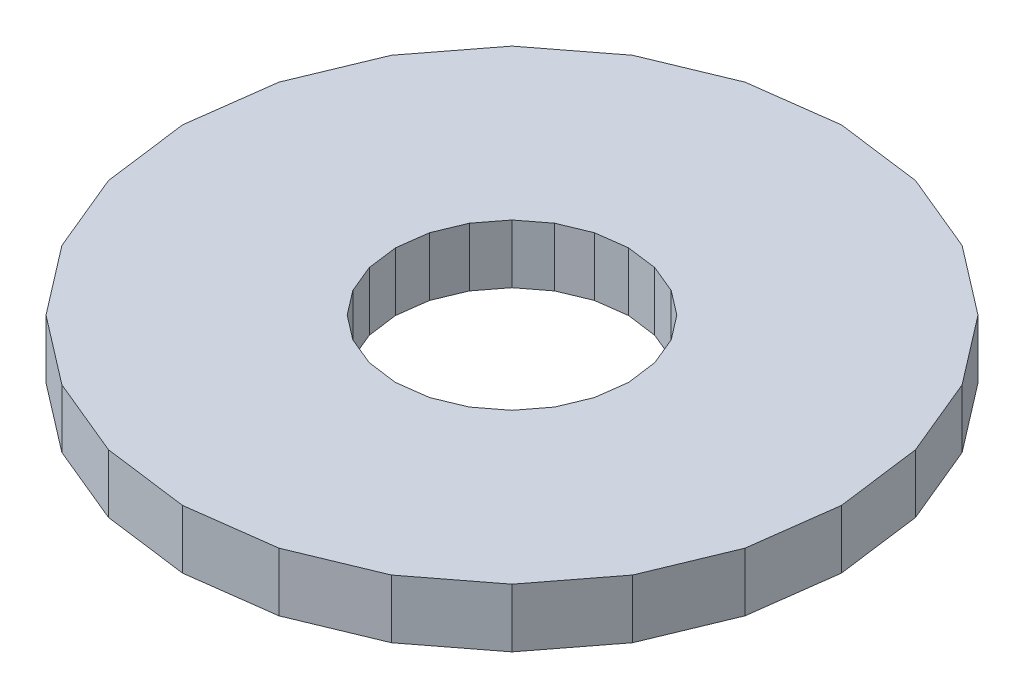
SolidWorks part; units mm, degrees
ref_plane "Front Plane" through (0, 0, 0) normal (0, 0, 1) x (1, 0, 0)
ref_plane "Top Plane" through (0, 0, 0) normal (0, 1, 0) x (1, 0, 0)
ref_plane "Right Plane" through (0, 0, 0) normal (1, 0, 0) x (0, 0, -1)
sketch "Sketch3" plane through (0, 0, 0) normal (0, 1, 0) x (1, 0, 0)
  line L0 (0, 0) -> (-37.8566, 0) construction
  line L1 (-107.0283, 0) -> (-103.3814, -27.701)
  line L2 (-103.3814, -27.701) -> (-92.6893, -53.5142)
  line L3 (-92.6893, -53.5142) -> (-75.6805, -75.6805)
  line L4 (-75.6805, -75.6805) -> (-53.5142, -92.6893)
  line L5 (-53.5142, -92.6893) -> (-27.701, -103.3814)
  line L6 (-27.701, -103.3814) -> (0, -107.0283)
  line L7 (0, -107.0283) -> (27.701, -103.3814)
  line L8 (27.701, -103.3814) -> (53.5142, -92.6893)
  line L9 (53.5142, -92.6893) -> (75.6805, -75.6805)
  line L10 (75.6805, -75.6805) -> (92.6893, -53.5142)
  line L11 (92.6893, -53.5142) -> (103.3814, -27.701)
  line L12 (103.3814, -27.701) -> (107.0283, 0)
  line L13 (107.0283, 0) -> (103.3814, 27.701)
  line L14 (103.3814, 27.701) -> (92.6893, 53.5142)
  line L15 (92.6893, 53.5142) -> (75.6805, 75.6805)
  line L16 (75.6805, 75.6805) -> (53.5142, 92.6893)
  line L17 (53.5142, 92.6893) -> (27.701, 103.3814)
  line L18 (27.701, 103.3814) -> (0, 107.0283)
  line L19 (0, 107.0283) -> (-27.701, 103.3814)
  line L20 (-27.701, 103.3814) -> (-53.5142, 92.6893)
  line L21 (-53.5142, 92.6893) -> (-75.6805, 75.6805)
  line L22 (-75.6805, 75.6805) -> (-92.6893, 53.5142)
  line L23 (-92.6893, 53.5142) -> (-103.3814, 27.701)
  line L24 (-103.3814, 27.701) -> (-107.0283, 0)
  line L25 (-37.8566, 0) -> (-36.5666, -9.798)
  line L26 (-36.5666, -9.798) -> (-32.7847, -18.9283)
  line L27 (-32.7847, -18.9283) -> (-26.7686, -26.7686)
  line L28 (-26.7686, -26.7686) -> (-18.9283, -32.7847)
  line L29 (-18.9283, -32.7847) -> (-9.798, -36.5666)
  line L30 (-9.798, -36.5666) -> (0, -37.8566)
  line L31 (0, -37.8566) -> (9.798, -36.5666)
  line L32 (9.798, -36.5666) -> (18.9283, -32.7847)
  line L33 (18.9283, -32.7847) -> (26.7686, -26.7686)
  line L34 (26.7686, -26.7686) -> (32.7847, -18.9283)
  line L35 (32.7847, -18.9283) -> (36.5666, -9.798)
  line L36 (36.5666, -9.798) -> (37.8566, 0)
  line L37 (37.8566, 0) -> (36.5666, 9.798)
  line L38 (36.5666, 9.798) -> (32.7847, 18.9283)
  line L39 (32.7847, 18.9283) -> (26.7686, 26.7686)
  line L40 (26.7686, 26.7686) -> (18.9283, 32.7847)
  line L41 (18.9283, 32.7847) -> (9.798, 36.5666)
  line L42 (9.798, 36.5666) -> (0, 37.8566)
  line L43 (0, 37.8566) -> (-9.798, 36.5666)
  line L44 (-9.798, 36.5666) -> (-18.9283, 32.7847)
  line L45 (-18.9283, 32.7847) -> (-26.7686, 26.7686)
  line L46 (-26.7686, 26.7686) -> (-32.7847, 18.9283)
  line L47 (-32.7847, 18.9283) -> (-36.5666, 9.798)
  line L48 (-36.5666, 9.798) -> (-37.8566, 0)
  line L50 (-107.0283, 0) -> (-37.8566, 0) construction
  circle A0 centre (0, 0) radius 106.1127 construction
  circle A1 centre (0, 0) radius 37.5327 construction
  dimension "D1" = 27.94
  dimension "D2" = 68.58
extrude "Boss-Extrude3" add sketch "Sketch3" along normal blind 19.05
